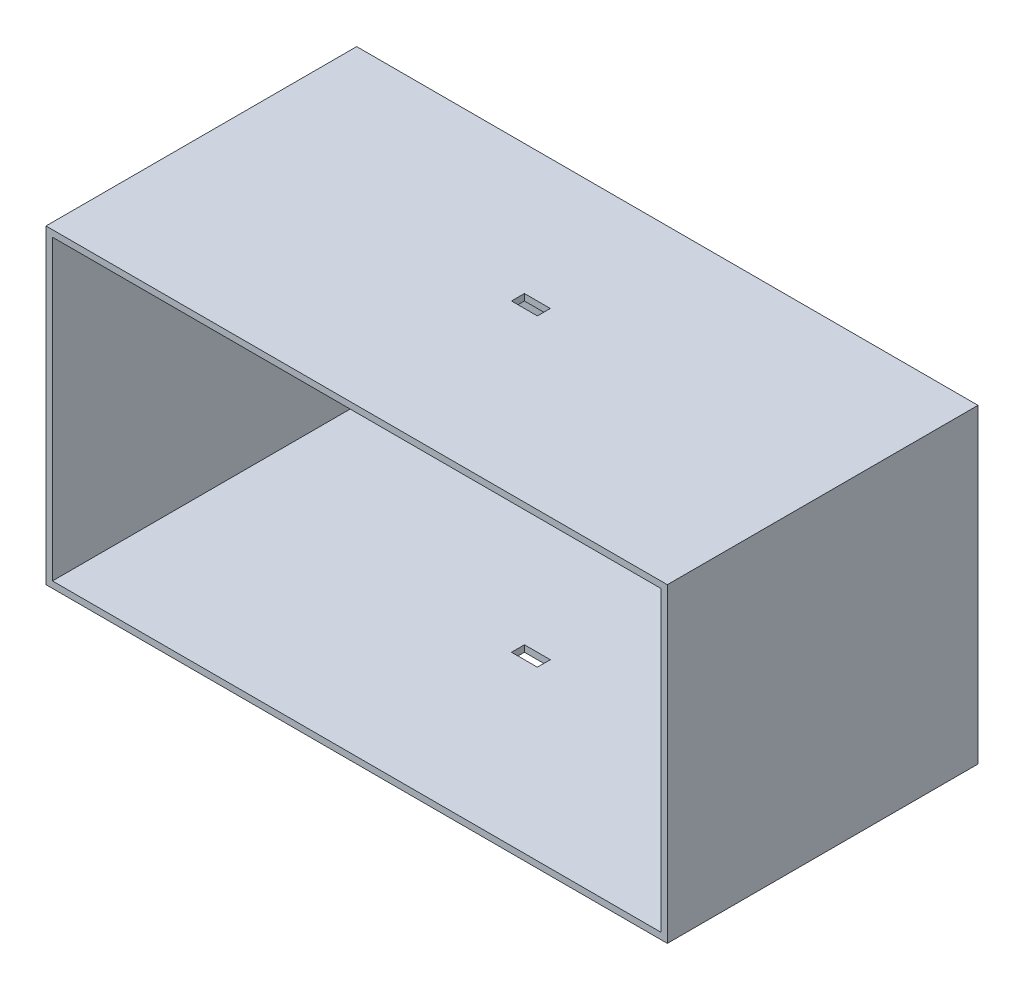
SolidWorks part; units mm, degrees
ref_plane "Front Plane" through (0, 0, 0) normal (0, 0, 1) x (1, 0, 0)
ref_plane "Top Plane" through (0, 0, 0) normal (0, 1, 0) x (1, 0, 0)
ref_plane "Right Plane" through (0, 0, 0) normal (1, 0, 0) x (0, 0, -1)
sketch "Sketch2" plane through (0, 0, 0) normal (0, 0, 1) x (1, 0, 0)
  line L1 (0, 0) -> (304.8, 0)
  line L2 (0, 0) -> (0, 152.4)
  line L3 (0, 152.4) -> (304.8, 152.4)
  line L4 (304.8, 0) -> (304.8, 152.4)
  dimension "D1" = 304.8
  dimension "D2" = 152.4
extrude "Boss-Extrude1" add sketch "Sketch2" along normal blind 152.4
shell "Shell1" thickness 3.175
sketch "Sketch3" plane through (0, 0, 0) normal (0, -1, 0) x (1, 0, 0)
  line L0 (152.4, 152.4) -> (152.4, 0) construction
  line L1 (0, 152.4) -> (304.8, 152.4) construction
  line L2 (0, 0) -> (304.8, 0) construction
  line L3 (152.4, 70.104) -> (152.4, 63.754) construction
  line L4 (146.05, 70.104) -> (158.75, 70.104)
  line L5 (146.05, 70.104) -> (146.05, 63.754)
  line L6 (146.05, 63.754) -> (158.75, 63.754)
  line L7 (158.75, 70.104) -> (158.75, 63.754)
  dimension "D1" = 88.646
  dimension "D2" = 12.7
  dimension "D3" = 6.35
extrude "Cut-Extrude1" cut sketch "Sketch3" against normal through all
equation "\"modulus\"= 435000"
equation "\"safety_factor\"= 3.5"
equation "\"tensile\"= 2.5"
equation "\"axial\"= 7.5"
equation "\"yield\"= 7250"
equation "\"w\"= 0.25"
equation "\"b\"= 0.5"
equation "\"deflection\"= 0.125"
equation "\"length\"= ( ( \"deflection\" * 3 * \"modulus\" * \"b\" * \"w\" ^ 3 ) / ( 12 * \"tensile\" ) ) ^ ( 1 / 3 )"
equation "\"area\"= \"b\" * \"w\""
